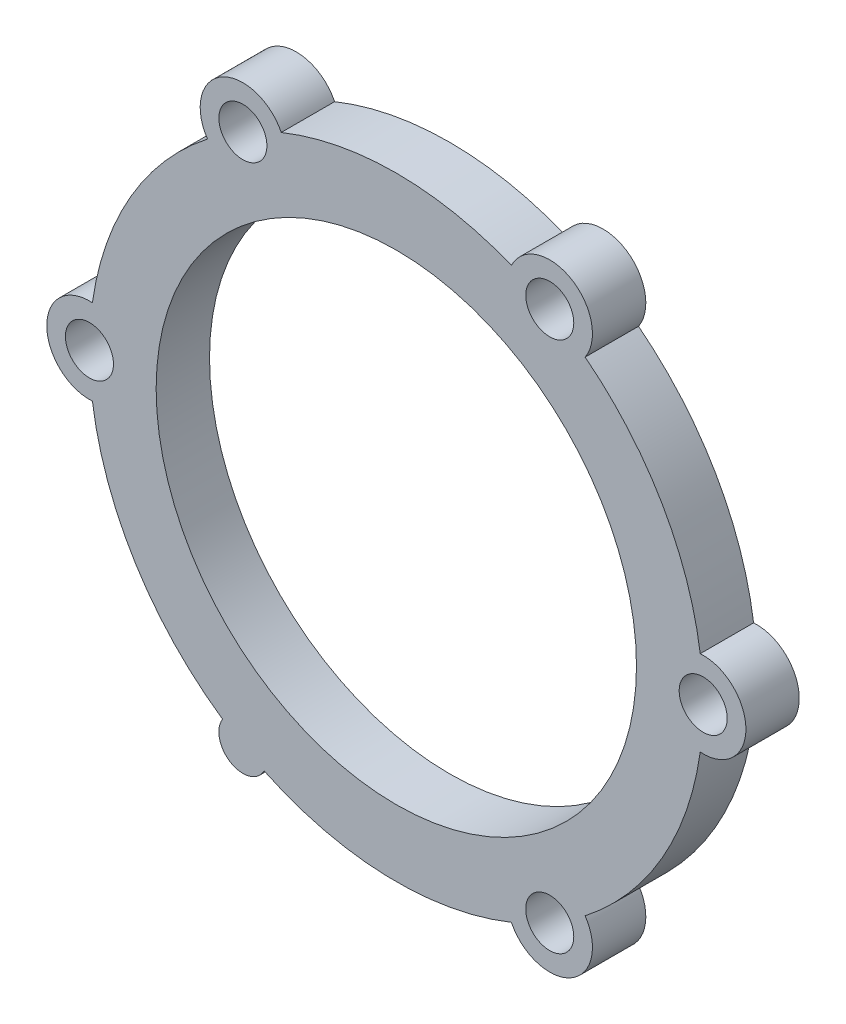
SolidWorks part; units mm, degrees
ref_plane "Front Plane" through (0, 0, 0) normal (0, 0, 1) x (1, 0, 0)
ref_plane "Top Plane" through (0, 0, 0) normal (0, 1, 0) x (1, 0, 0)
ref_plane "Right Plane" through (0, 0, 0) normal (1, 0, 0) x (0, 0, -1)
sketch "Sketch1" plane through (0, 0, 0) normal (0, 0, 1) x (1, 0, 0)
  line L0 (-61.1894, 0) -> (58.1702, 0) construction
  line L1 (28.75, 49.7965) -> (0, 0) construction
  circle A0 centre (0, 0) radius 45
  circle A1 centre (0, 0) radius 57.5
  circle A3 centre (-57.5, 0) radius 8
  circle A4 centre (-57.5, 0) radius 4.5
  circle A5 centre (-28.75, 49.7965) radius 8
  circle A6 centre (-28.75, 49.7965) radius 4.5
  circle A7 centre (28.75, 49.7965) radius 8
  circle A8 centre (28.75, 49.7965) radius 4.5
  circle A9 centre (57.5, 0) radius 8
  circle A10 centre (57.5, 0) radius 4.5
  circle A11 centre (28.75, -49.7965) radius 8
  circle A12 centre (28.75, -49.7965) radius 4.5
  circle A13 centre (-28.75, -49.7965) radius 8
  circle A14 centre (-28.75, -49.7965) radius 4.5
  point P27 (0, 0)
  dimension "D1" = 9
  dimension "D2" = 16
  dimension "D3" = 90
  dimension "D4" = 115
  dimension "D5" = 60
extrude "Boss-Extrude1" add sketch "Sketch1" along normal blind 10 contours A8 A1 A7 | A13 A1 A11 A9 A7 A5 A3 A0 | A8 A1 A7 | A10 A1 A9 | A10 A1 A9 | A12 A1 A11 | A12 A1 A11 | A14 A1 A13 | A4 A1 A3 | A4 A1 A3 | A6 A1 A5 | A6 A1 A5
